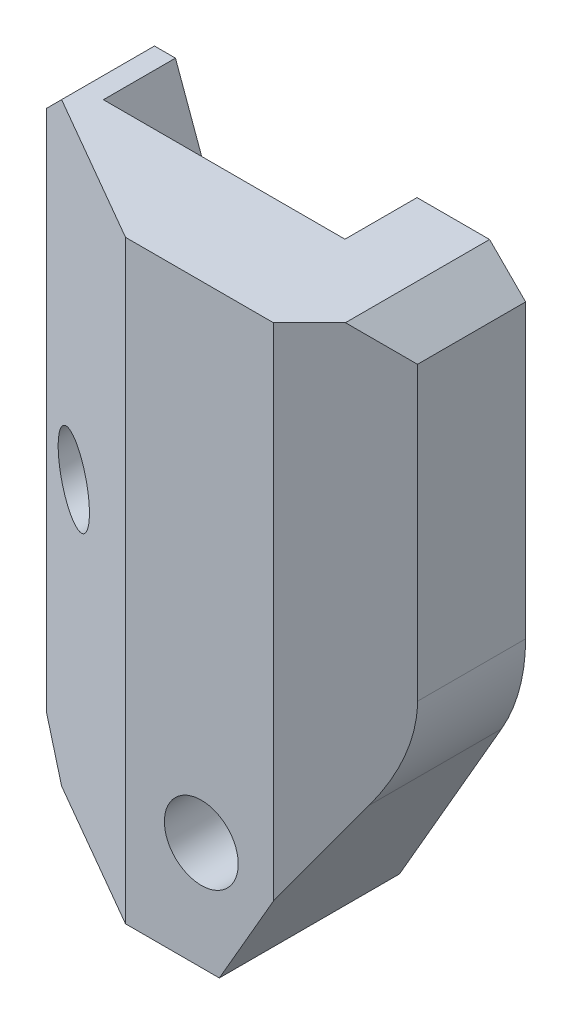
SolidWorks part; units mm, degrees
material "普通碳钢"
ref_plane "前视基准面" through (0, 0, 0) normal (0, 0, 1) x (1, 0, 0)
ref_plane "上视基准面" through (0, 0, 0) normal (0, 1, 0) x (1, 0, 0)
ref_plane "右视基准面" through (0, 0, 0) normal (1, 0, 0) x (0, 0, -1)
sketch "草图1" plane through (0, 0, 0) normal (0, 0, 1) x (1, 0, 0)
  line L0 (0, 10) -> (0, -10) construction
  line L1 (-2.5, 10) -> (2.5, 10)
  line L2 (-2.5, 10) -> (-2.5, -10)
  line L3 (-2.5, -10) -> (2.5, -10)
  line L4 (2.5, 10) -> (2.5, -10)
  dimension "D1" = 5
  dimension "D2" = 20
extrude "拉伸1" add sketch "草图1" along normal blind 5
sketch "Sketch1" plane through (-2.5, 0, 0) normal (-1, 0, 0) x (0, 0, 1)
  line L4 (0, 10) -> (0, -10)
  line L5 (0, -10) -> (5, -10)
  line L6 (5, -10) -> (5, 10)
  line L7 (5, 10) -> (0, 10)
  line L8 (0, 10) -> (0, -10)
  line L9 (0, -10) -> (5, -10)
  line L10 (5, -10) -> (5, 10)
  line L11 (5, 10) -> (0, 10)
  dimension "D1" = 0
extrude "Extrude1" add sketch "Sketch1" along normal blind 6.8
sketch "草图2" plane through (0, 0, 5) normal (0, 0, 1) x (1, 0, 0)
  line L0 (-1.5, 7) -> (-1.5, -7)
  line L1 (-1.5, 0) -> (-7, 0)
  line L2 (0, 0) -> (-1.5, 0)
  line L3 (2.5, -10) -> (2.5, 10) construction
  line L4 (-1.5, -2) -> (-7, -2)
  dimension "D1" = 14
  dimension "D2" = 5.5
  dimension "D3" = 4
  dimension "D4" = 5.5
  dimension "D5" = 5
hole_wizard "M2.5 Tapped Hole1" positions "3D草图1" profile "草图3" tap size "M2.5" standard "GB"
sketch3d "3D草图1"
  point P3 (-1.5, -7, 5)
  point P7 (-7, -2, 5)
sketch "草图3" plane through (-1.5, -7, 5) normal (1, 0, 0) x (0, -1, 0)
  line L0 (0, 0) -> (0, 6.9659)
  line L1 (0, 6.9659) -> (1.025, 6.35)
  line L2 (1.025, 6.35) -> (1.025, 0)
  line L5 (1.025, 0) -> (0, 0)
  line L10 (0, 6.9659) -> (-1.025, 6.35) construction
  line L11 (0, -6.35) -> (0, 107.95) construction
  dimension "Tap Drill Dia." = 2.05
  dimension "Tap Drill Depth" = 6.35
  dimension "Drill Angle" = 118
cosmetic thread "Hole Thread1" parameters "D1"=3.4775, "D2"=2.5
cosmetic thread "Hole Thread2" parameters "D1"=5, "D2"=2.5
chamfer "倒角1" [suppressed] distance 0.5 angle 45
sketch "Sketch2" plane through (0, 0, 0) normal (0, 0, -1) x (-1, 0, 0)
  line L0 (-2.3835, -1.4598) -> (0.0791, 5.306)
  line L1 (1.3608, 5.9037) -> (5.4014, 4.433)
  line L2 (5.9991, 3.1513) -> (3.5366, -3.6145)
  line L3 (2.2549, -4.2122) -> (-1.7858, -2.7415)
  line L4 (1.5, 0) -> (3.3811, 5.1683) construction
  line L5 (-2.5, -10) -> (-2.5, 10) construction
  line L6 (1.5, 0) -> (7, 0) construction
  arc A0 (-1.7858, -2.7415) -> (-2.3835, -1.4598) centre (-1.4438, -1.8018) cw
  arc A1 (3.5366, -3.6145) -> (2.2549, -4.2122) centre (2.5969, -3.2725) cw
  arc A2 (5.4014, 4.433) -> (5.9991, 3.1513) centre (5.0594, 3.4933) cw
  arc A3 (0.0791, 5.306) -> (1.3608, 5.9037) centre (1.0188, 4.964) cw
  dimension "D2" = 1
  dimension "D1" = 20
  dimension "D3" = 6.3
  dimension "D4" = 9.2
  dimension "D5" = 5.5
  dimension "D6" = 4
extrude "Extrude2" cut sketch "Sketch2" against normal blind 2
chamfer "Chamfer1" distance 2 angle 45 1 edges at (2.5, 0, 5)
sketch "Sketch3" plane through (0, 0, 5) normal (0, 0, 1) x (1, 0, 0)
  line L0 (2.5, 10) -> (2.5, -10) construction
  line L1 (-9.3, 10) -> (2.5, 10)
  line L2 (-9.3, 10) -> (-9.3, 6.5)
  line L3 (-9.3, 6.5) -> (2.5, 6.5)
  line L4 (2.5, 10) -> (2.5, 6.5)
  dimension "D1" = 3.5
extrude "Extrude3" cut sketch "Sketch3" against normal up to surface (5 mm away)
sketch "Sketch4" plane through (0, 0, 0) normal (0, 0, -1) x (-1, 0, 0)
  line L0 (-0.263, 4.3663) -> (1.4471, 9.0648)
  line L1 (0.0791, 5.306) -> (-2.3835, -1.4598) construction
  line L2 (1.4471, 9.0648) -> (7.3672, 6.91)
  line L3 (7.3672, 6.91) -> (5.6571, 2.2116)
  line L4 (3.5366, -3.6145) -> (5.9991, 3.1513) construction
  line L5 (5.6571, 2.2116) -> (-0.263, 4.3663)
  line L6 (5.4014, 4.433) -> (1.3608, 5.9037) construction
  dimension "D1" = 2
  dimension "D2" = 5
extrude "Extrude4" cut sketch "Sketch4" against normal up to surface (2 mm away) up to face at (-1.8078, 0.8457, 2)
chamfer "Chamfer2" distance 1 angle 45 1 edges at (-9.3, 6.5, 2.5)
chamfer "Chamfer3" [suppressed] distance 7 angle 45
sketch "Sketch7" [suppressed] plane through (0, 0, 3) normal (0, 0, 1) x (1, 0, 0)
  line L0 (-9.3, -10) -> (-9.3, 5.5) construction
  line L1 (-7, -2.5) -> (-9.3, -2.5)
  line L2 (-7, -2.5) -> (-7, 2.5)
  line L3 (-7, 2.5) -> (-9.3, 2.5)
  line L4 (-9.3, -2.5) -> (-9.3, 2.5)
  arc A0 (-9.3, -0.9798) -> (-9.3, 0.9798) centre (-7, 0) ccw construction
  arc A1 (-9.3, -0.9798) -> (-9.3, 0.9798) centre (-7, 0) ccw construction
  circle A2 centre (-7, 0) radius 1.45 construction
  circle A3 centre (-7, 0) radius 1.45 construction
extrude "Extrude5" [suppressed] cut sketch "Sketch7" along normal up to surface (2 mm away)
chamfer "Chamfer4" distance 3.5 angle 60 1 edges at (2.5, -10, 1.5)
chamfer "Chamfer5" [suppressed] distance 0.5 angle 45
sketch "Sketch8" plane through (0, 0, 5) normal (0, 0, 1) x (1, 0, 0)
  line L0 (-8.3, 6.5) -> (0.5, 6.5) construction
  line L1 (-9.3, -10) -> (-8.3, -10)
  line L2 (-9.3, -10) -> (-9.3, 6.5)
  line L3 (-9.3, 6.5) -> (-8.3, 6.5)
  line L4 (-8.3, -10) -> (-8.3, 6.5)
  dimension "D1" = 1
extrude "Extrude6" cut sketch "Sketch8" against normal blind 10
chamfer "Chamfer6" [suppressed] distance 2 angle 45
sketch "Sketch11" plane through (-8.3, 0, 0) normal (-1, 0, 0) x (0, 0, 1)
  line L4 (0, -10) -> (5, -10)
  line L5 (5, -10) -> (5, 6.5)
  line L6 (5, 6.5) -> (0, 6.5)
  line L7 (0, 6.5) -> (0, -10)
  line L8 (0, -10) -> (5, -10)
  line L9 (5, -10) -> (5, 6.5)
  line L10 (5, 6.5) -> (0, 6.5)
  line L11 (0, 6.5) -> (0, -10)
  dimension "D1" = 0
extrude "Extrude8" add sketch "Sketch11" along normal blind 0.5
sketch "Sketch10" plane through (0, 6.5, 0) normal (0, 1, 0) x (1, 0, 0)
  line L0 (-8.8, -2) -> (-3.6038, -5)
  line L2 (-8.8, -5) -> (0.5, -5) construction
  line L3 (-3.6038, -5) -> (-8.8, -5)
  line L4 (-8.8, -5) -> (-8.8, -2)
  line L5 (-8.8, -5) -> (-8.8, 0) construction
  dimension "D1" = 60
  dimension "D2" = 3
extrude "Extrude7" cut sketch "Sketch10" against normal up to surface (16.5 mm away) up to face at (-4.9, -10, 2.5)
chamfer "Chamfer7" distance 1 angle 45 3 edges at (2.5, 6.5, 1.5) (-8.8, 6.5, 1) (-8.8, -10, 1)
fillet "Fillet1" radius 5 1 edges at (2.5, -3.9378, 1.5)
